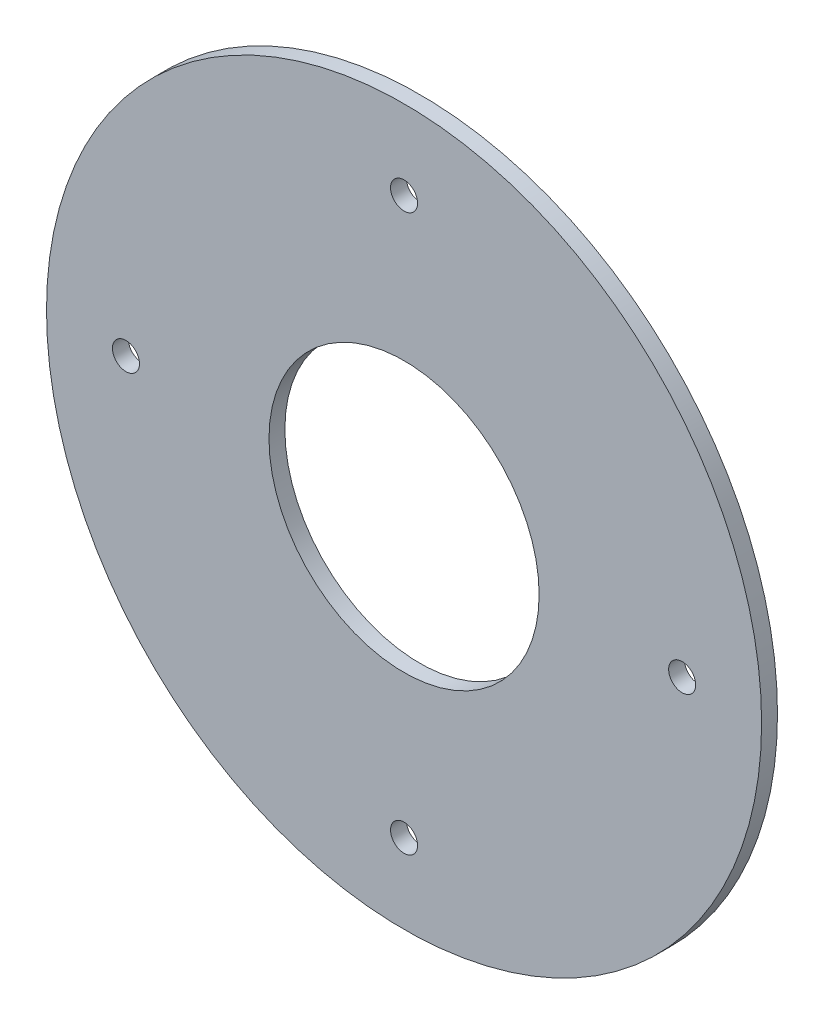
SolidWorks part; units mm, degrees
ref_plane "Спереди" through (0, 0, 0) normal (0, 0, 1) x (1, 0, 0)
ref_plane "Сверху" through (0, 0, 0) normal (0, 1, 0) x (1, 0, 0)
ref_plane "Справа" through (0, 0, 0) normal (1, 0, 0) x (0, 0, -1)
sketch "Эскиз1" plane through (0, 0, 0) normal (0, 0, 1) x (1, 0, 0)
  circle A0 centre (0, 0) radius 45
  circle A1 centre (0, 0) radius 17
  dimension "D1" = 90
  dimension "D2" = 34
extrude "Бобышка-Вытянуть1" add sketch "Эскиз1" along normal blind 2
sketch "Эскиз2" plane through (0, 0, 2) normal (0, 0, 1) x (1, 0, 0)
  line L0 (-45, 0) -> (45, 0) construction
  line L1 (0, 45) -> (0, -45) construction
  circle A0 centre (0, 0) radius 45 construction
  circle A1 centre (0, 0) radius 35 construction
  dimension "D1" = 70
hole_wizard "Отверстие с зазором M31" positions "Эскиз4" profile "Эскиз3" hole size "M3" standard "Ansi Metric" end condition through all
sketch "Эскиз4" plane through (0, 0, 2) normal (0, 0, 1) x (1, 0, 0)
  line L0 (0, 45) -> (0, -45) construction
  line L1 (-45, 0) -> (45, 0) construction
  circle A0 centre (0, 0) radius 35 construction
  point P0 (0, 35)
  point P6 (-35, 0)
  point P10 (0, -35)
  point P12 (35, 0)
sketch "Эскиз3" plane through (0, 35, 2) normal (1, 0, 0) x (0, -1, 0)
  line L0 (0, 0) -> (0, 2)
  line L1 (0, 2) -> (1.7, 2)
  line L2 (1.7, 2) -> (1.7, 0)
  line L5 (1.7, 0) -> (0, 0)
  line L11 (0, -6.35) -> (0, 107.95) construction
  dimension "Диаметр сквозного отверстия" = 3.4
  dimension "Глубина сквозного отверстия" = 2
